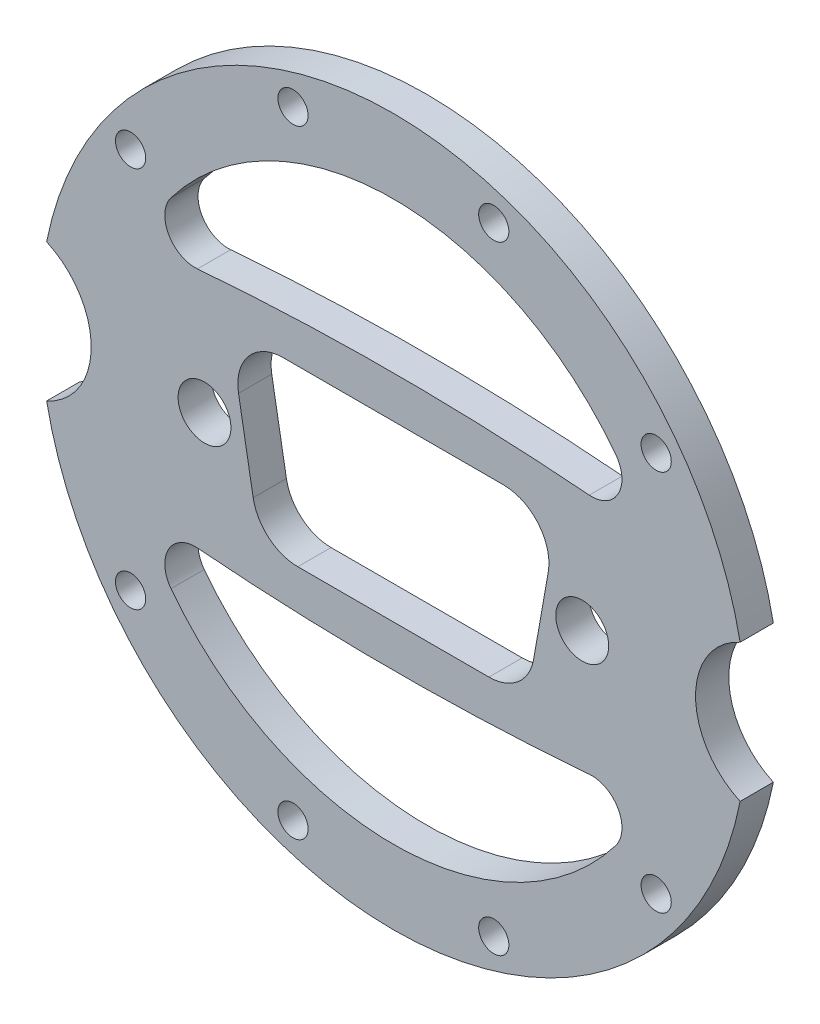
SolidWorks part; units mm, degrees
material "2014 Legierung"
ref_plane "Vorne" through (0, 0, 0) normal (0, 0, 1) x (1, 0, 0)
ref_plane "Oben" through (0, 0, 0) normal (0, 1, 0) x (1, 0, 0)
ref_plane "Rechts" through (0, 0, 0) normal (1, 0, 0) x (0, 0, -1)
sketch "Skizze1" plane through (0, 0, 0) normal (0, 0, 1) x (1, 0, 0)
  line L0 (-12.9673, 8) -> (12.9673, 8) construction
  line L2 (0, 0) -> (33.7788, 0) construction
  line L4 (-12.9673, -8) -> (12.9673, -8) construction
  line L5 (-6.6439, 20.4477) -> (0, 0) construction
  line L6 (-12.9673, 8) -> (12.9673, 8) construction
  line L7 (0, 0) -> (0, 25.2877) construction
  line L8 (-12.9673, -8) -> (12.9673, -8) construction
  circle A0 centre (0, 0) radius 23.4
  arc A1 (14.7209, 11.2047) -> (-14.7209, 11.2047) centre (0, 0) ccw
  arc A2 (-14.7209, -11.2047) -> (14.7209, -11.2047) centre (0, 0) ccw
  arc A3 (-12.9673, 8) -> (-14.7209, 11.2047) centre (-13.1294, 9.9934) cw
  arc A4 (12.9673, 8) -> (14.7209, 11.2047) centre (13.1294, 9.9934) ccw
  arc A5 (-12.9673, -8) -> (-14.7209, -11.2047) centre (-13.1294, -9.9934) ccw
  arc A6 (12.9673, -8) -> (14.7209, -11.2047) centre (13.1294, -9.9934) cw
  circle A7 centre (6.6439, 20.4477) radius 1
  circle A8 centre (17.3939, 12.6374) radius 1
  circle A10 centre (17.3939, -12.6374) radius 1
  arc A11 (-12.9673, 8) -> (12.9673, 8) centre (0, -151.4737) cw
  arc A12 (-12.9673, -8) -> (12.9673, -8) centre (0, 151.4737) ccw
  circle A13 centre (-6.6439, 20.4477) radius 1
  circle A14 centre (6.6439, -20.4477) radius 1
  circle A15 centre (-6.6439, -20.4477) radius 1
  circle A16 centre (-17.3939, -12.6374) radius 1
  circle A18 centre (-17.3939, 12.6374) radius 1
  circle A47 centre (-21.5, 0) radius 1 [skipped]
  circle A48 centre (21.5, 0) radius 1 [skipped]
  dimension "D1" = 37
  dimension "D2" = 46.8
  dimension "D3" = 2
  dimension "D6" = 160
  dimension "D7" = 21.5
  dimension "D8" = 2
  dimension "D5" = 16
  dimension "D9" = 18
extrude "Linear austragen1" add sketch "Skizze1" along normal blind 2.2
sketch "Skizze3" plane through (0, 0, 2.2) normal (0, 0, 1) x (1, 0, 0)
  line L0 (0, 0) -> (0, 13.9221) construction
  line L1 (-7.2956, 5.75) -> (7.2956, 5.75)
  line L2 (-10.25, 2.2291) -> (-9.2802, -3.2709)
  line L3 (-6.3258, -5.75) -> (6.3258, -5.75)
  line L4 (10.25, 2.2291) -> (9.2802, -3.2709)
  line L5 (0, 0) -> (3.5223, 0) construction
  circle A0 centre (12.5, 0) radius 1.75
  circle A1 centre (-12.5, 0) radius 1.75
  arc A2 (7.2956, 5.75) -> (10.25, 2.2291) centre (7.2956, 2.75) cw
  arc A3 (6.3258, -5.75) -> (9.2802, -3.2709) centre (6.3258, -2.75) ccw
  arc A4 (-9.2802, -3.2709) -> (-6.3258, -5.75) centre (-6.3258, -2.75) ccw
  arc A5 (-7.2956, 5.75) -> (-10.25, 2.2291) centre (-7.2956, 2.75) ccw
  dimension "D1" = 3.5
  dimension "D5" = 3
  dimension "D2" = 25
  dimension "D3" = 80
  dimension "D4" = 11.5
  dimension "D6" = 20.5
extrude "Schnitt-Linear austragen3" cut sketch "Skizze3" against normal through all
sketch "Sketch1" plane through (0, 0, 0) normal (0, 0, 1) x (1, 0, 0)
  line L0 (-28.4164, 0) -> (28.4164, 0) construction
  circle A0 centre (-25, 0) radius 5
  circle A1 centre (25, 0) radius 5
  dimension "D3" = 10
  dimension "D4" = 10
  dimension "D1" = 25
  dimension "D2" = 25
extrude "Cut-Extrude1" cut sketch "Sketch1" along normal blind 3
